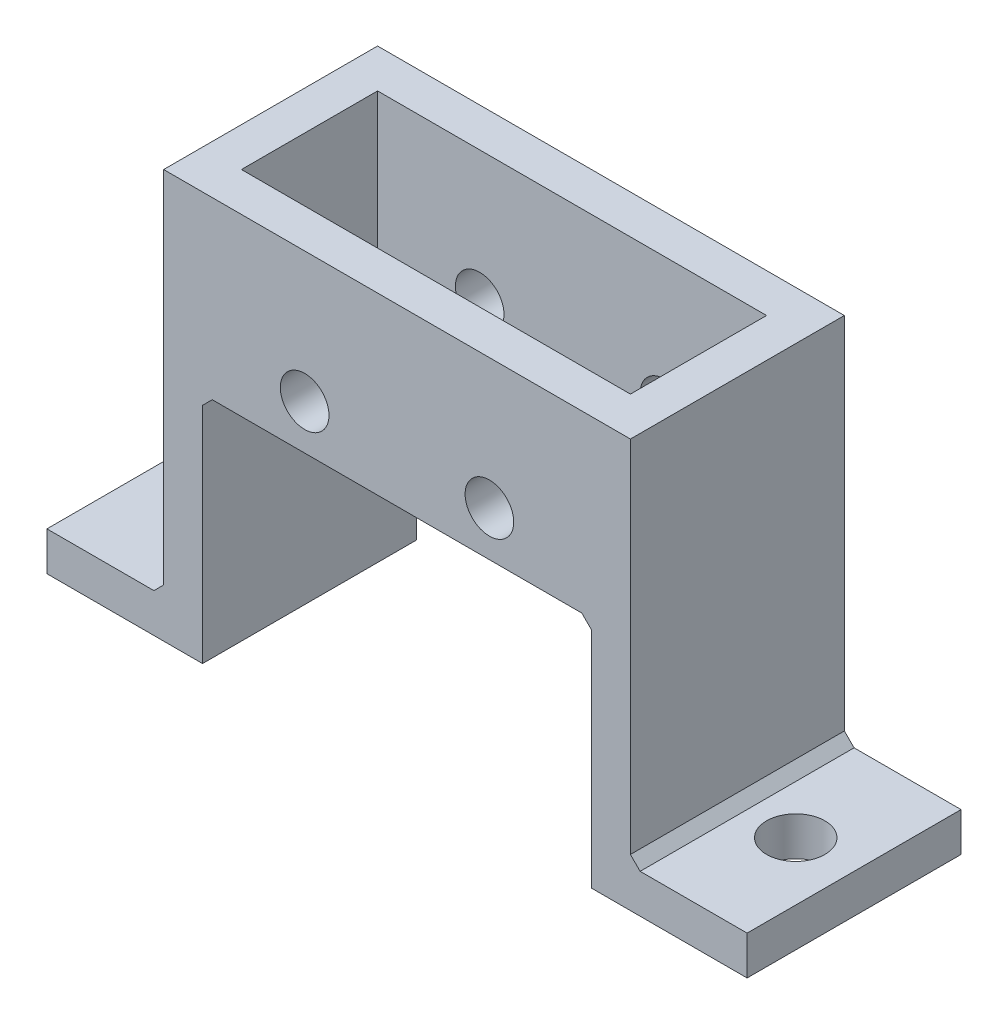
SolidWorks part; units mm, degrees
ref_plane "Alzado" through (0, 0, 0) normal (0, 0, 1) x (1, 0, 0)
ref_plane "Planta" through (0, 0, 0) normal (0, 1, 0) x (1, 0, 0)
ref_plane "Vista lateral" through (0, 0, 0) normal (1, 0, 0) x (0, 0, -1)
sketch "Croquis1" plane through (0, 0, 0) normal (0, 0, 1) x (1, 0, 0)
  line L0 (0, 0) -> (20, 0)
  line L1 (20, 0) -> (20, 10)
  line L2 (20, 0) -> (10, 0) construction
  line L3 (10, 0) -> (10, 2.3) construction
  line L4 (5.25, 2.3) -> (14.75, 2.3)
  line L5 (20, 10) -> (0, 10)
  line L6 (0, 10) -> (0, 0)
  circle A0 centre (5.25, 2.3) radius 1.25
  circle A1 centre (14.75, 2.3) radius 1.25
  point P9 (10, 2.3)
  dimension "D4" = 2.5
  dimension "D5" = 2.5
  dimension "D1" = 20
  dimension "D2" = 2.3
  dimension "D3" = 9.5
  dimension "D6" = 10
extrude "Saliente-Extruir1" add sketch "Croquis1" along normal blind 2 contours L6 L0 L1 L5 | A0 | A1
sketch "Croquis2" plane through (0, 0, 2) normal (0, 0, 1) x (1, 0, 0)
  line L0 (0, 10) -> (-2, 10)
  line L1 (-2, 10) -> (-2, 0)
  line L2 (-2, 0) -> (0, 0)
  line L3 (20, 10) -> (22, 10)
  line L4 (22, 10) -> (22, 0)
  line L5 (22, 0) -> (20, 0)
  line L6 (0, 10) -> (0, 0)
  line L7 (20, 10) -> (20, 0)
  dimension "D1" = 2
  dimension "D2" = 2
extrude "Saliente-Extruir2" add sketch "Croquis2" against normal blind 11
sketch "Croquis3" plane through (0, 0, -9) normal (0, 0, -1) x (-1, 0, 0)
  line L1 (-20, 10) -> (0, 10)
  line L2 (-20, 10) -> (-20, 0)
  line L3 (-20, 0) -> (0, 0)
  line L4 (0, 10) -> (0, 0)
  circle A0 centre (-5.25, 2.3) radius 1.25 construction
  circle A1 centre (-14.75, 2.3) radius 1.25 construction
  circle A2 centre (-5.25, 2.3) radius 1.25
  circle A3 centre (-14.75, 2.3) radius 1.25
extrude "Saliente-Extruir3" add sketch "Croquis3" against normal blind 2 separate body
sketch "Croquis4" plane through (0, 0, 0) normal (0, -1, 0) x (1, 0, 0)
  line L1 (-2, 2) -> (0, 2)
  line L2 (-2, 2) -> (-2, -9)
  line L3 (-2, -9) -> (0, -9)
  line L4 (0, 2) -> (0, -9)
  line L5 (22, 2) -> (20, 2)
  line L6 (22, 2) -> (22, -9)
  line L7 (22, -9) -> (20, -9)
  line L8 (20, 2) -> (20, -9)
extrude "Saliente-Extruir4" add sketch "Croquis4" along normal blind 12
sketch "Croquis5" plane through (22, 0, 0) normal (1, 0, 0) x (0, 0, -1)
  line L0 (9, -12) -> (9, 10) construction
  line L1 (-2, -12) -> (9, -12)
  line L2 (-2, -12) -> (-2, -10)
  line L3 (-2, -10) -> (9, -10)
  line L4 (9, -12) -> (9, -10)
  dimension "D1" = 2
extrude "Saliente-Extruir5" add sketch "Croquis5" along normal blind 6
sketch "Croquis6" plane through (-2, 0, 0) normal (-1, 0, 0) x (0, 0, 1)
  line L0 (2, 10) -> (2, -12) construction
  line L1 (-9, -12) -> (2, -12)
  line L2 (-9, -12) -> (-9, -10)
  line L3 (-9, -10) -> (2, -10)
  line L4 (2, -12) -> (2, -10)
  dimension "D1" = 2
extrude "Saliente-Extruir6" add sketch "Croquis6" along normal blind 6
sketch "Croquis7" plane through (0, 10, 0) normal (0, 1, 0) x (1, 0, 0)
  line L1 (-2, 9) -> (22, 9)
  line L2 (-2, 9) -> (-2, -2)
  line L3 (-2, -2) -> (22, -2)
  line L4 (22, 9) -> (22, -2)
  line L5 (20, 0) -> (0, 0)
  line L6 (20, 0) -> (20, 7)
  line L7 (20, 7) -> (0, 7)
  line L8 (0, 0) -> (0, 7)
extrude "Cortar-Extruir1" cut sketch "Croquis7" against normal blind 1
sketch "Croquis8" plane through (0, -10, 0) normal (0, 1, 0) x (1, 0, 0)
  line L0 (-8, 9) -> (-2, 9) construction
  line L1 (-2, 9) -> (-5, 9) construction
  line L2 (-5, 9) -> (-5, -2) construction
  line L3 (-8, -2) -> (-2, -2) construction
  line L4 (-5, -2) -> (-5, 3.5) construction
  line L5 (22, 9) -> (28, 9) construction
  line L6 (28, 9) -> (22, 9) construction
  line L7 (28, 9) -> (25, 9) construction
  line L8 (25, 9) -> (25, -2) construction
  line L9 (28, -2) -> (22, -2) construction
  line L10 (25, -2) -> (25, 3.5) construction
  circle A0 centre (-5, 3.5) radius 1.5
  circle A1 centre (25, 3.5) radius 1.5
  dimension "D1" = 3
  dimension "D2" = 3
extrude "Cortar-Extruir2" cut sketch "Croquis8" against normal blind 11
chamfer "Chaflán1" distance 0.5 angle 45 6 edges at (0, 0, -8) (0, 0, 1) (20, 0, 1) (20, 0, -8) (-2, -10, -3.5) (22, -10, -3.5)
